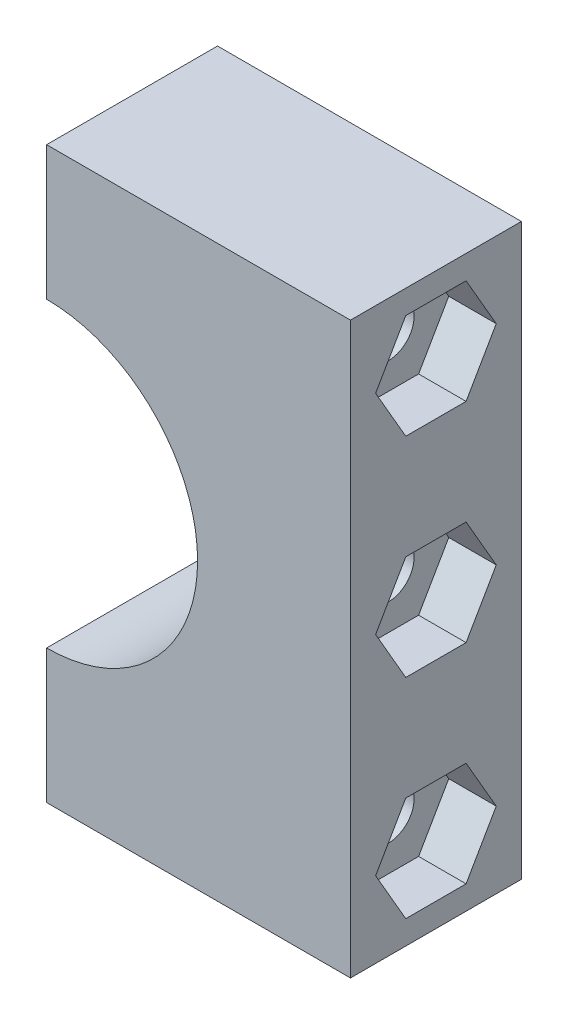
SolidWorks part; units mm, degrees
material "ABS"
ref_plane "Ön Düzlem" through (0, 0, 0) normal (0, 0, 1) x (1, 0, 0)
ref_plane "Üst Düzlem" through (0, 0, 0) normal (0, 1, 0) x (1, 0, 0)
ref_plane "Sağ Düzlem" through (0, 0, 0) normal (1, 0, 0) x (0, 0, -1)
sketch "Çizim1" plane through (0, 0, 0) normal (0, 0, 1) x (1, 0, 0)
  line L0 (16, 0) -> (16, 30) construction
  line L9 (0, 0) -> (32, 0)
  line L11 (0, 30) -> (32, 30)
  line L17 (27.5, 15) -> (4.5, 15) construction
  line L18 (0, 30) -> (0, 22)
  line L19 (0, 22) -> (0.5, 22)
  line L20 (4.5, 18) -> (4.5, 12)
  line L21 (0.5, 8) -> (0, 8)
  line L22 (0, 8) -> (0, 0)
  line L23 (32, 30) -> (32, 22)
  line L24 (32, 22) -> (31.5, 22)
  line L25 (27.5, 18) -> (27.5, 12)
  line L26 (31.5, 8) -> (32, 8)
  line L27 (32, 8) -> (32, 0)
  circle A0 centre (16, 15) radius 7.95
  arc A1 (0.5, 22) -> (4.5, 18) centre (0.5, 18) cw
  arc A2 (4.5, 12) -> (0.5, 8) centre (0.5, 12) cw
  arc A3 (31.5, 22) -> (27.5, 18) centre (31.5, 18) ccw
  arc A4 (27.5, 12) -> (31.5, 8) centre (31.5, 12) ccw
  point P21 (32, 26)
  point P22 (32, 4)
  point P27 (27.5, 22)
  dimension "D1" = 15.9
  dimension "D6" = 4
  dimension "D2" = 8
  dimension "D3" = 22
  dimension "D4" = 32
  dimension "D5" = 4.5
extrude "Yükseklik-Ekstrüzyon1" add sketch "Çizim1" along normal blind 8
sketch "Çizim2" plane through (32, 0, 0) normal (1, 0, 0) x (0, 0, -1)
  line L0 (0, 26) -> (-8, 26) construction
  line L1 (-4, 30) -> (-4, 22) construction
  line L2 (-8, 4) -> (0, 4) construction
  line L3 (-4, 8) -> (-4, 0) construction
  line L4 (0, 22) -> (0, 30)
  line L5 (0, 30) -> (-8, 30)
  line L6 (-8, 30) -> (-8, 22)
  line L7 (-8, 22) -> (0, 22)
  line L8 (0, 22) -> (0, 30) construction
  line L9 (0, 30) -> (-8, 30) construction
  line L10 (-8, 30) -> (-8, 22) construction
  line L11 (-8, 22) -> (0, 22) construction
  line L14 (0, 0) -> (0, 8)
  line L15 (0, 8) -> (-8, 8)
  line L16 (-8, 8) -> (-8, 0)
  line L17 (-8, 0) -> (0, 0)
  line L18 (0, 0) -> (0, 8) construction
  line L19 (0, 8) -> (-8, 8) construction
  line L20 (-8, 8) -> (-8, 0) construction
  line L21 (-8, 0) -> (0, 0) construction
  circle A0 centre (-4, 4) radius 1.35
  circle A1 centre (-4, 26) radius 1.35
  dimension "D3" = 2.7
  dimension "D2" = 0
  dimension "D1" = 0
extrude "Kes-Ekstrüzyon1" cut sketch "Çizim2" against normal blind 50
sketch "Çizim3" plane through (4.5, 0, 0) normal (-1, 0, 0) x (0, 0, 1)
  line L0 (4, 30) -> (4, 0) construction
  line L1 (8, 30) -> (0, 30) construction
  line L2 (8, 0) -> (0, 0) construction
  circle A0 centre (4, 15) radius 1.35
  dimension "D1" = 2.7
extrude "Kes-Ekstrüzyon2" cut sketch "Çizim3" against normal blind 29
sketch "Çizim4" plane through (0, 0, 0) normal (0, 0, -1) x (-1, 0, 0)
  line L0 (-16, 30) -> (-16, 0)
  line L1 (-32, 30) -> (0, 30) construction
  line L2 (0, 0) -> (-32, 0) construction
  line L6 (-16, 30) -> (11.8438, 39.5316)
  line L7 (11.8438, 39.5316) -> (11.8438, 24.557)
  line L8 (9.2411, -10.2785) -> (-16, 0)
  line L9 (9.2411, -10.2785) -> (11.8438, 24.557)
extrude "Kes-Ekstrüzyon3" cut sketch "Çizim4" against normal blind 10
sketch "Çizim5" plane through (0, 0, 0) normal (0, 0, -1) x (-1, 0, 0)
  line L0 (-32, 22) -> (-26.4702, 22)
  line L1 (-26.4702, 22) -> (-26.4702, 5.4506)
  line L2 (-26.4702, 5.4506) -> (-32, 5.4506)
  line L3 (-32, 0) -> (-32, 8) construction
  line L4 (-32, 5.4506) -> (-32, 22)
extrude "Yükseklik-Ekstrüzyon2" add sketch "Çizim5" against normal up to surface (8 mm away) up to face at (26.3578, 15, 8)
sketch "Çizim6" plane through (26.4702, 0, 0) normal (-1, 0, 0) x (0, 0, 1)
  circle A0 centre (4, 15) radius 1.35
  dimension "D1" = 2.7
extrude "Kes-Ekstrüzyon4" cut sketch "Çizim6" against normal blind 10
sketch "Çizim7" plane through (32, 0, 0) normal (1, 0, 0) x (0, 0, -1)
  line L0 (-8, 30) -> (0, 30) construction
  line L1 (-2.4123, 28.75) -> (-5.5877, 28.75)
  line L2 (-5.5877, 28.75) -> (-7.1754, 26)
  line L3 (-7.1754, 26) -> (-5.5877, 23.25)
  line L4 (-5.5877, 23.25) -> (-2.4123, 23.25)
  line L5 (-2.4123, 23.25) -> (-0.8246, 26)
  line L6 (-0.8246, 26) -> (-2.4123, 28.75)
  line L7 (-0.8246, 15) -> (-2.4123, 17.75)
  line L8 (-2.4123, 17.75) -> (-5.5877, 17.75)
  line L9 (-5.5877, 17.75) -> (-7.1754, 15)
  line L10 (-7.1754, 15) -> (-5.5877, 12.25)
  line L11 (-5.5877, 12.25) -> (-2.4123, 12.25)
  line L12 (-2.4123, 12.25) -> (-0.8246, 15)
  line L13 (-2.4123, 6.75) -> (-5.5877, 6.75)
  line L14 (-5.5877, 6.75) -> (-7.1754, 4)
  line L15 (-7.1754, 4) -> (-5.5877, 1.25)
  line L16 (-5.5877, 1.25) -> (-2.4123, 1.25)
  line L17 (-2.4123, 1.25) -> (-0.8246, 4)
  line L18 (-0.8246, 4) -> (-2.4123, 6.75)
  line L19 (-8, 15) -> (0, 15) construction
  line L20 (-8, 0) -> (-8, 30) construction
  line L21 (0, 0) -> (0, 30) construction
  line L22 (0, 4) -> (-8, 4) construction
  circle A0 centre (-4, 26) radius 2.75 construction
  circle A1 centre (-4, 15) radius 2.75 construction
  circle A2 centre (-4, 4) radius 2.75 construction
  dimension "D1" = 5.5
  dimension "D2" = 5.5
  dimension "D3" = 5.5
extrude "Kes-Ekstrüzyon5" cut sketch "Çizim7" against normal blind 2.5
ref_plane "Düzlem1" through (0, 0, 4) normal (0, 0, 1) x (1, 0, 0)
sketch "Çizim8" plane through (0, 0, 8) normal (0, 0, 1) x (1, 0, 0)
  line L0 (32, 30) -> (32, 0)
  line L20 (32, 0) -> (32, 30)
  line L21 (32, 30) -> (16, 30)
  line L22 (16, 30) -> (16, 22.95)
  line L23 (16, 7.05) -> (16, 0)
  line L24 (16, 0) -> (32, 0)
  line L38 (32, 30) -> (16, 30)
  line L39 (16, 30) -> (16, 22.95)
  line L40 (16, 7.05) -> (16, 0)
  line L41 (16, 0) -> (32, 0)
  arc A1 (16, 7.05) -> (16, 22.95) centre (16, 15) ccw
  arc A2 (16, 7.05) -> (16, 22.95) centre (16, 15) ccw
  dimension "D1" = 0
extrude "Yükseklik-Ekstrüzyon3" add sketch "Çizim8" along normal blind 0.5
mirror "Aynalama1" about plane through (0, 0, 4) normal (0, 0, 1) of "Yükseklik-Ekstrüzyon3"
